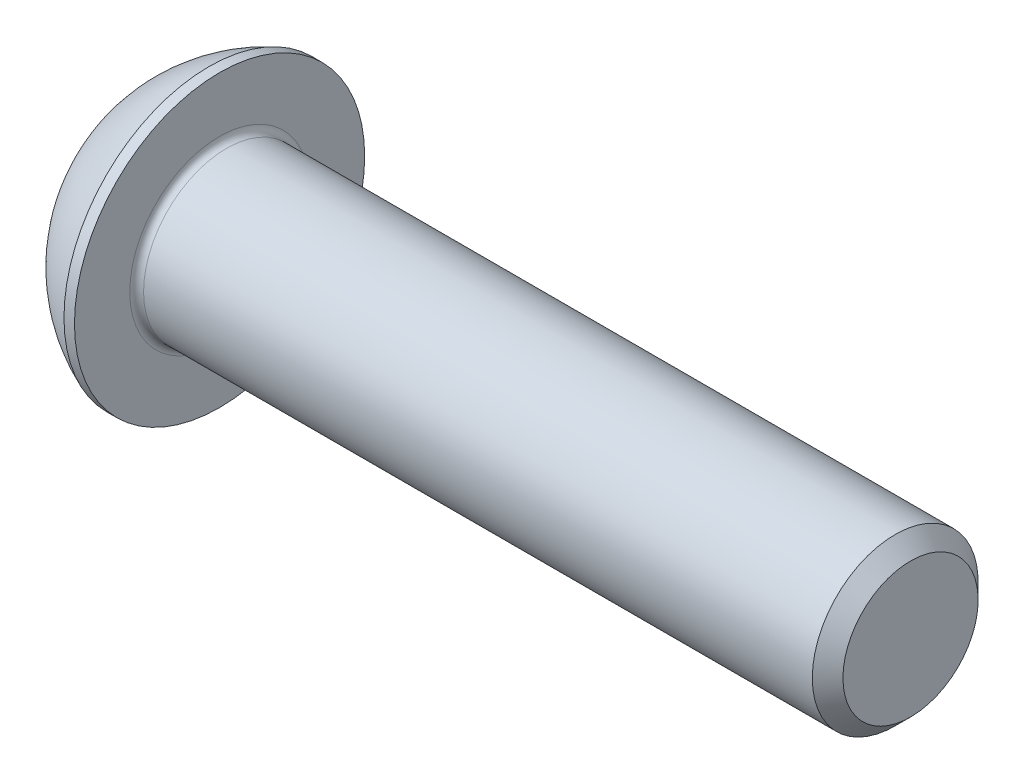
SolidWorks part; units mm, degrees
ref_plane "Plane1" through (0, 0, 0) normal (0, 0, 1) x (1, 0, 0)
ref_plane "Plane2" through (0, 0, 0) normal (0, 1, 0) x (1, 0, 0)
ref_plane "Plane3" through (0, 0, 0) normal (1, 0, 0) x (0, 0, -1)
sketch "BodySke" plane through (0, 0, 0) normal (0, 0, 1) x (1, 0, 0)
  line L0 (28.3, 0) -> (28.3, 2.4455)
  line L1 (27.7455, 3) -> (3.3, 3)
  line L2 (3.3, 3) -> (3.3, 5.25)
  line L3 (3.3, 5.25) -> (2.92, 5.25)
  line L4 (0, 0) -> (101.6, 0) construction
  line L5 (3.3, -5.25) -> (2.92, -5.25) construction
  line L6 (55.6768, -3) -> (3.3, -3) construction
  line L7 (28.3, 0) -> (0, 0)
  line L8 (0, 2.625) -> (0, -2.625) construction
  line L9 (0, 0) -> (0, 2.625)
  line L10 (28.3, 2.4455) -> (27.7455, 3)
  line L11 (28.3, -2.4455) -> (27.7455, -3) construction
  line L12 (4.3, 9.525) -> (4.3, -3) construction
  line L13 (3.3, 9.525) -> (3.3, -3) construction
  arc A1 (0, 2.625) -> (2.92, 5.25) centre (4.9997, 0) cw
  dimension "Diameter" = 6
  dimension "Length" = 25
  dimension "Head_dia" = 10.5
  dimension "D1" = 5.25
  dimension "Head_ht" = 3.3
  dimension "Head_side_ht" = 0.38
  dimension "Minor_dia" = 4.891
  dimension "Body_ch_ang" = 45
  dimension "Advance" = 1
  dimension "Thread_nom" = 25
revolve "BaseBody" add sketch "BodySke" angle 360 about L4
cosmetic thread "ThreadCosmetic" [suppressed] parameters "Thread_length"=23, "Thread_minor"=4.891
fillet "Fillet1" radius 0.25 1 edges at (3.3, 0, 3)
sketch "Sketch2" plane through (0, 0, 0) normal (0, 0, 1) x (1, 0, 0)
  line L0 (0, 2) -> (2.08, 2)
  line L1 (2.08, 2) -> (3.2347, 0)
  line L3 (3.2347, 0) -> (0, 0)
  line L4 (0, 0) -> (0, 2)
  line L5 (0, -2) -> (2.08, -2) construction
  line L6 (0, 0) -> (47.625, 0) construction
  dimension "D2" = 60
  dimension "PreBroach_depth" = 2.08
  dimension "PreBroach_dia" = 4
revolve "PreBroach" cut sketch "Sketch2" angle 360 about L6
sketch "Sketch3" plane through (0, 0, 0) normal (1, 0, 0) x (0, 0, -1)
  line L0 (-2, -1.1547) -> (-2, 1.1547)
  line L1 (-2, 1.1547) -> (0, 2.3094)
  line L2 (0, 2.3094) -> (2, 1.1547)
  line L3 (2, 1.1547) -> (2, -1.1547)
  line L4 (2, -1.1547) -> (0, -2.3094)
  line L5 (0, -2.3094) -> (-2, -1.1547)
  dimension "Hex_size" = 4
  dimension "D3" = 4
  dimension "D1" = 2
  dimension "D2" = 2
extrude "Hex" cut sketch "Sketch3" along normal blind 2.08
sketch "ThdSchSke" plane through (0, 0, 0) normal (0, 0, 1) x (1, 0, 0)
  line L0 (5.3, -2.4455) -> (4.9117, -3)
  line L1 (5.3, -2.4455) -> (5.6883, -3)
  line L2 (5.6883, -3) -> (5.6883, -3.75)
  line L3 (-3.175, 0) -> (5.1513, 0) construction
  line L5 (5.6883, -3.75) -> (4.9117, -3.75)
  line L6 (4.9117, -3.75) -> (4.9117, -3)
  dimension "Diameter" = 6
  dimension "Thread_minor" = 4.891
  dimension "SideAngle" = 55
  dimension "VeeAngle" = 70
  dimension "Overcut" = 7.5
  dimension "Start" = 5.3
revolve "ThreadSchematic" [suppressed] cut sketch "ThdSchSke" angle 360 about L3
pattern_linear "ThdSchPat" [suppressed]
equation "\"D1@BodySke\" = \"Head_dia@BodySke\" * .5"
equation "\"Thread_minor@ThreadCosmetic\" = \"Minor_dia@BodySke\""
equation "\"D1@Sketch3\" = \"Hex_size@Sketch3\" / 2"
equation "\"D2@Sketch3\" = \"D1@Sketch3\""
equation "\"D3@Sketch3\" = \"Hex_size@Sketch3\""
equation "\"Thread_length@ThreadCosmetic\" = ((sgn( (\"Length@BodySke\" - \"Advance@BodySke\" * 2.0) - \"Thread_nom@BodySke\" )-1)*( (\"Length@BodySke\" - \"Advance@BodySke\" * 2.0) - \"Thread_nom@BodySke\" ))/-2+ \"Thread_nom@BodySke\""
equation "\"Thread_minor@ThdSchSke\" = \"Minor_dia@BodySke\""
equation "\"Diameter@ThdSchSke\" = \"Diameter@BodySke\""
equation "\"Overcut@ThdSchSke\" = \"Diameter@BodySke\" * 1.25"
equation "\"Start@ThdSchSke\" = \"Head_ht@BodySke\" + \"Length@BodySke\" - \"Thread_length@ThreadCosmetic\"  '---Non-countersunk---"
equation "\"Num_threads@ThdSchPat\" = int( \"Thread_length@ThreadCosmetic\" / \"Advance@BodySke\" + 0.999 )  + 1"
equation "\"Advance@ThdSchPat\" = \"Thread_length@ThreadCosmetic\" /  (\"Num_threads@ThdSchPat\" - 1) 'relax it"
equation "\"Num_threads@ThdSchPat\" = \"Num_threads@ThdSchPat\" - sgn( \"Num_threads@ThdSchPat\" - 1) '---chamfered tips only---"
